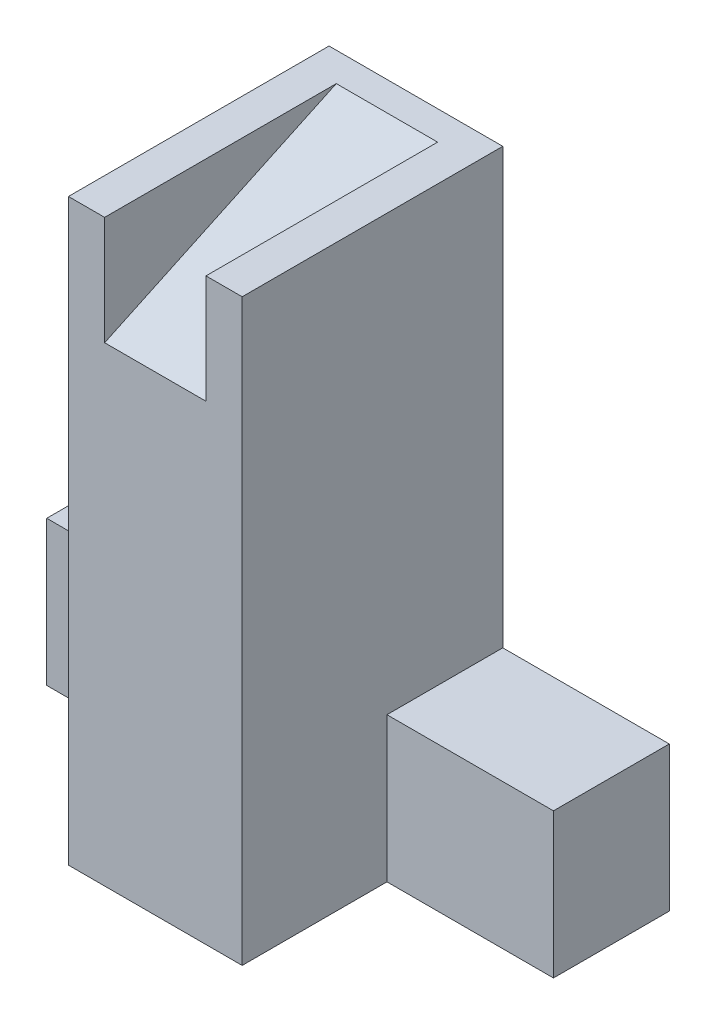
SolidWorks part; units mm, degrees
ref_plane "Front Plane" through (0, 0, 0) normal (0, 0, 1) x (1, 0, 0)
ref_plane "Top Plane" through (0, 0, 0) normal (0, 1, 0) x (1, 0, 0)
ref_plane "Right Plane" through (0, 0, 0) normal (1, 0, 0) x (0, 0, -1)
sketch "Sketch1" plane through (0, 0, 0) normal (0, 0, 1) x (1, 0, 0)
  line L1 (0, 0) -> (24000, 0)
  line L2 (0, 0) -> (0, 80000)
  line L3 (0, 80000) -> (24000, 80000)
  line L4 (24000, 0) -> (24000, 80000)
  dimension "D1" = 24000
  dimension "D2" = 80000
extrude "Boss-Extrude1" add sketch "Sketch1" along normal blind 36000
sketch "Sketch2" plane through (24000, 0, 0) normal (1, 0, 0) x (0, 0, -1)
  line L0 (-36000, 80000) -> (-4000, 80000)
  line L1 (-36000, 80000) -> (0, 80000) construction
  line L2 (-4000, 80000) -> (-36000, 65000)
  line L3 (-36000, 0) -> (-36000, 80000) construction
  line L4 (-36000, 65000) -> (-36000, 80000)
  dimension "D1" = 15000
  dimension "D2" = 32000
extrude "Cut-Extrude1" cut sketch "Sketch2" against normal blind 14000 from offset 5000 offset against normal yes
sketch "Sketch3" plane through (0, 0, 0) normal (0, 0, -1) x (-1, 0, 0)
  line L1 (-24000, 0) -> (-47000, 0)
  line L2 (-24000, 0) -> (-24000, 20000)
  line L3 (-24000, 20000) -> (-47000, 20000)
  line L4 (-47000, 0) -> (-47000, 20000)
  line L5 (0, 0) -> (23000, 0)
  line L6 (0, 0) -> (0, 20000)
  line L7 (0, 20000) -> (23000, 20000)
  line L8 (23000, 0) -> (23000, 20000)
  dimension "D1" = 20000
  dimension "D2" = 20000
  dimension "D3" = 23000
  dimension "D4" = 23000
extrude "Boss-Extrude2" add sketch "Sketch3" against normal blind 16000
